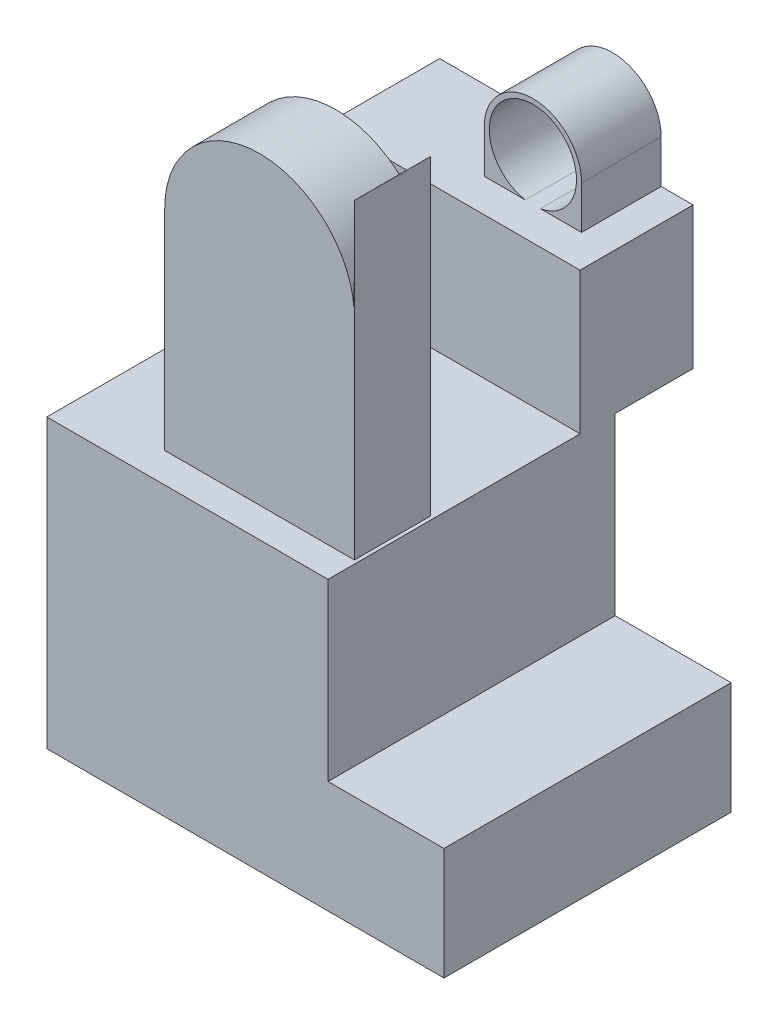
SolidWorks part; units mm, degrees
ref_plane "前视基准面" through (0, 0, 0) normal (0, 0, 1) x (1, 0, 0)
ref_plane "上视基准面" through (0, 0, 0) normal (0, 1, 0) x (1, 0, 0)
ref_plane "右视基准面" through (0, 0, 0) normal (1, 0, 0) x (0, 0, -1)
sketch "草图1" plane through (0, 0, 0) normal (0, 0, 1) x (1, 0, 0)
  line L1 (30.6814, -0.7642) -> (59.9139, -0.7642)
  line L2 (-40.2025, -0.7642) -> (-40.2025, -29.0414)
  line L3 (-40.2025, -29.0414) -> (59.9139, -29.0414)
  line L4 (59.9139, -0.7642) -> (59.9139, -29.0414)
  line L6 (30.6814, -0.7642) -> (30.6814, 43.3711)
  line L7 (30.6814, 43.3711) -> (-40.2025, 43.3711)
  line L8 (-40.2025, -0.7642) -> (-40.2025, 43.3711)
extrude "凸台-拉伸1" add sketch "草图1" along normal blind 72.39
sketch "草图2" plane through (0, 43.3711, 0) normal (0, 1, 0) x (1, 0, 0)
  line L1 (30.6814, -8.8504) -> (-33.2131, -8.8504)
  line L2 (30.6814, -8.8504) -> (30.6814, 41.7343)
  line L3 (30.6814, 41.7343) -> (-33.2131, 41.7343)
  line L4 (-33.2131, -8.8504) -> (-33.2131, 41.7343)
  line L5 (-33.2131, 136.6999) -> (-33.2131, 48.9189) construction
extrude "凸台-拉伸2" add sketch "草图2" along normal up to surface (35.7235 mm away)
sketch "草图3" plane through (0, 43.3711, 0) normal (0, 1, 0) x (1, 0, 0)
  line L1 (-18.0355, -45.6369) -> (29.7816, -45.6369)
  line L2 (-18.0355, -45.6369) -> (-18.0355, -64.8362)
  line L3 (-18.0355, -64.8362) -> (29.7816, -64.8362)
  line L4 (29.7816, -45.6369) -> (29.7816, -64.8362)
  point P4 (-18.0355, -64.8362)
extrude "凸台-拉伸4" add sketch "草图3" along normal blind 78.486
sketch "草图6" plane through (0, 0, 64.8362) normal (0, 0, 1) x (1, 0, 0)
  line L0 (-18.0355, 121.8571) -> (-18.0355, 43.3711) construction
  line L1 (29.7816, 121.8571) -> (29.7816, 43.3711) construction
  line L2 (-18.0355, 96.2331) -> (-18.0355, 124.9972)
  line L3 (-18.0355, 124.9972) -> (29.7816, 124.9972)
  line L4 (29.7816, 124.9972) -> (29.7173, 94.4809)
  arc A0 (29.7173, 94.4809) -> (-18.0355, 96.2331) centre (5.873, 96.2331) ccw
  line M3 (29.7816, 121.8571) -> (-18.0355, 121.8571)
  line M4 (-18.0355, 121.8571) -> (-18.0355, 43.3711)
extrude "切除-拉伸4" cut sketch "草图6" against normal blind 22.098 contours A0 L4 M3 M4
sketch "草图7" plane through (0, 0, -41.7343) normal (0, 0, -1) x (-1, 0, 0)
  line L0 (-33.6814, 36.7358) -> (-33.6814, 39.7358) construction
  line L1 (-33.6814, 36.7358) -> (51.4501, 36.7358)
  line L2 (-33.6814, 36.7358) -> (-33.6814, 80.3263)
  line L3 (-33.6814, 80.3263) -> (51.4501, 80.3263)
  line L4 (51.4501, 36.7358) -> (51.4501, 80.3263)
  line L5 (-33.6814, -0.7642) -> (-33.6814, 53.2358) construction
extrude "切除-拉伸5" cut sketch "草图7" against normal blind 22.098
sketch "草图8" plane through (0, 0, -19.6363) normal (0, 0, -1) x (-1, 0, 0)
  line L0 (-22.6336, 89.929) -> (-22.6336, 79.0946)
  line L1 (33.2131, 79.0946) -> (-30.6814, 79.0946) construction
  line L2 (-22.6336, 79.0946) -> (-22.6336, 75.392)
  line L3 (-22.6336, 75.392) -> (1.9064, 75.392)
  line L4 (1.9064, 75.392) -> (1.8787, 90.7525)
  circle A0 centre (-10.3636, 89.929) radius 11
  arc A1 (1.8816, 89.1496) -> (-22.6336, 89.929) centre (-10.3636, 89.929) ccw
  circle A3 centre (-10.3636, 89.929) radius 12.27 construction
  point P12 (1.9064, 89.929)
  line M3 (33.2131, 79.0946) -> (-30.6814, 79.0946)
  dimension "D1" = 1.27
extrude "凸台-拉伸5" add sketch "草图8" against normal blind 20.066 contours L4 A1 L0 A0 M3 | A0 L2 L3 L4 M3
